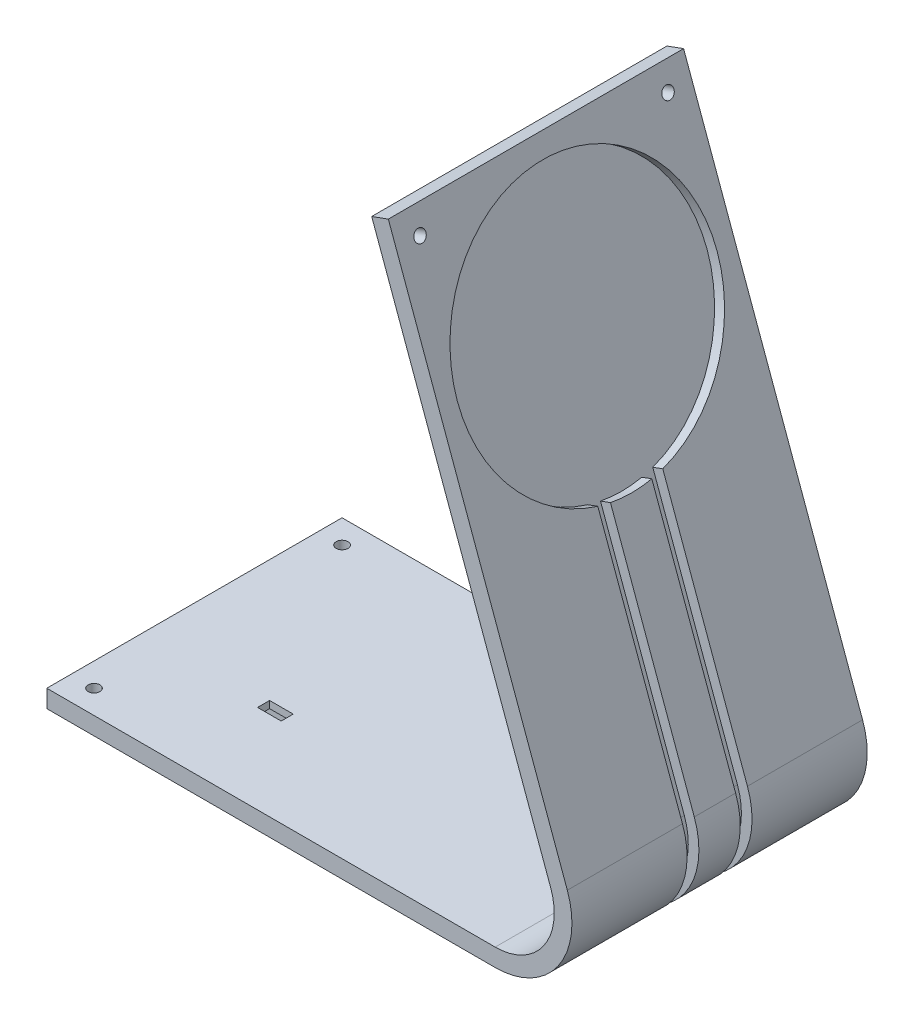
SolidWorks part; units mm, degrees
ref_plane "前视基准面" through (0, 0, 0) normal (0, 0, 1) x (1, 0, 0)
ref_plane "上视基准面" through (0, 0, 0) normal (0, 1, 0) x (1, 0, 0)
ref_plane "右视基准面" through (0, 0, 0) normal (1, 0, 0) x (0, 0, -1)
other "Configuration Table"
sketch "草图2" plane through (0, 0, 0) normal (0, 0, 1) x (1, 0, 0)
  line L0 (-42.6188, 0) -> (33.3109, 0)
  line L5 (42.7078, 13.4202) -> (12.3985, 96.6944)
  line L6 (42.7078, 13.4202) -> (9.2861, 105.2456) construction
  line L7 (-42.6188, -5) -> (-42.6188, 0) construction
  line L8 (33.3109, 0) -> (33.3109, -1) construction
  line L10 (15.2773, 97.8486) -> (12.3643, 96.7883) construction
  line L11 (-42.6188, 0) -> (33.3109, 0) construction
  arc A0 (33.3109, 0) -> (42.7078, 13.4202) centre (33.3109, 10) ccw
  dimension "D2" = 10
  dimension "D1" = 0.1
extrude "整体拉伸-薄壁1" add sketch "草图2" along normal mid plane 50 thin
sketch "草图4" plane through (44.8442, 16.3219, 0) normal (0.9397, 0.342, 0) x (0, 0, -1)
  line L0 (-25, 86.6225) -> (25, 86.6225) construction
  circle A0 centre (0, 61.2225) radius 22
  dimension "D1" = 44
  dimension "D2" = 25.4
extrude "中间圆切除-拉伸1" cut sketch "草图4" against normal blind 1.8
sketch "草图3" plane through (0, 0, 0) normal (0, 0, 1) x (1, 0, 0)
  line L0 (45.5269, 14.4463) -> (15.2176, 97.7204) construction
  line L1 (45.5269, 14.4463) -> (15.2176, 97.7204) construction
  line L2 (-42.6188, -3) -> (33.3109, -3) construction
  line L3 (-42.6188, -3) -> (33.3109, -3) construction
  line L4 (8.763, -1.2) -> (33.3109, -1.2)
  line L5 (43.8354, 13.8306) -> (29.7379, 52.5634)
  line L6 (43.8354, 13.8306) -> (13.5261, 97.1048) construction
  line L7 (-42.6188, -1.2) -> (33.3109, -1.2) construction
  line L9 (29.7379, 52.5634) -> (31.4293, 53.179) construction
  line L16 (29.7379, 52.5634) -> (28.7118, 55.3824)
  arc A0 (33.3109, 0) -> (42.7078, 13.4202) centre (33.3109, 10) ccw construction
  arc A1 (33.3109, -3) -> (45.5269, 14.4463) centre (33.3109, 10) ccw construction
  arc A2 (33.3109, -1.2) -> (43.8354, 13.8306) centre (33.3109, 10) ccw
  dimension "D2" = 3
  dimension "D1" = 1.8
extrude "线槽切除-拉伸-薄壁1" cut sketch "草图3" against normal blind 2 from offset 5.5 thin
mirror "镜向1" about plane through (0, 0, 0) normal (0, 0, 1) of "线槽切除-拉伸-薄壁1"
sketch "草图5" plane through (44.8442, 16.3219, 0) normal (0.9397, 0.342, 0) x (0, 0, -1)
  line L0 (-25, -1.9961) -> (-25, 86.6225) construction
  line L1 (-25, 86.6225) -> (25, 86.6225) construction
  circle A0 centre (-21, 82.6225) radius 1
  dimension "D1" = 2
  dimension "D3" = 4
  dimension "D2" = 4
extrude "螺丝孔切除-拉伸2" cut sketch "草图5" against normal up to next
mirror "镜向2" about plane through (0, 0, 0) normal (0, 0, 1) of "螺丝孔切除-拉伸2"
sketch "草图6" plane through (0, 0, 0) normal (0, 1, 0) x (1, 0, 0)
  line L0 (-42.6188, -25) -> (33.3109, -25) construction
  line L1 (-42.6188, -25) -> (-42.6188, 25) construction
  circle A0 centre (-38.6188, -21) radius 1
  dimension "D1" = 2
  dimension "D2" = 4
  dimension "D3" = 4
extrude "下螺丝孔切除-拉伸3" cut sketch "草图6" against normal up to next
mirror "镜向3" about plane through (0, 0, 0) normal (0, 0, 1) of "下螺丝孔切除-拉伸3"
sketch "草图7" plane through (0, -3, 0) normal (0, -1, 0) x (1, 0, 0)
  line L1 (-40.9188, -5.9) -> (-26.9188, -5.9)
  line L2 (-42.6188, -4.6) -> (-42.6188, 4.6)
  line L3 (-40.9188, 5.9) -> (-26.9188, 5.9)
  line L4 (-26.9188, -5.9) -> (-26.9188, 5.9)
  line L7 (-42.6188, -4.6) -> (-40.9188, -4.6)
  line L9 (-42.6188, 4.6) -> (-40.9188, 4.6)
  line L11 (-40.9188, 4.6) -> (-40.9188, 5.9)
  line L12 (-40.9188, -4.6) -> (-40.9188, -5.9)
  line L14 (-34.1188, -4.5) -> (-41.6188, -4.5) construction
  line L15 (-42.6188, 25) -> (-42.6188, -25) construction
  line L18 (-27.0188, 5.8) -> (-40.8188, 5.8) construction
  line L19 (-40.8188, -5.8) -> (-27.0188, -5.8) construction
  line L20 (-27.0188, -5.8) -> (-27.0188, 5.8) construction
  line L21 (-40.8188, 5.8) -> (-40.8188, 4.5) construction
  dimension "D1" = 0.1
  dimension "D2" = 9.2
  dimension "D3" = 0.1
  dimension "D4" = 0.1
  dimension "D5" = 0.1
  dimension "D6" = 0.1
extrude "切除-拉伸1" cut sketch "草图7" against normal blind 1.8
sketch "草图8" plane through (0, -1.2, 0) normal (0, -1, 0) x (1, 0, 0)
  line L1 (-42.6188, -4.6) -> (-40.9188, -4.6)
  line L2 (-42.6188, -4.6) -> (-42.6188, 4.6)
  line L3 (-42.6188, 4.6) -> (-40.9188, 4.6)
  line L4 (-40.9188, -4.6) -> (-40.9188, 4.6)
extrude "凸台-拉伸1" add sketch "草图8" along normal blind 1.7
sketch "草图12" plane through (0, -3, 0) normal (0, -1, 0) x (1, 0, 0)
  line L1 (-10.1, -8.1) -> (-10.1, -10.6)
  line L2 (-10.1, -10.6) -> (15.1, -10.6)
  line L3 (15.1, -10.6) -> (15.1, 10.6)
  line L4 (15.1, 10.6) -> (-10.1, 10.6)
  line L5 (-13.1, 8.1) -> (-13.1, -8.1)
  line L7 (-13.1, -8.1) -> (-10.1, -8.1)
  line L8 (-13.1, 8.1) -> (-10.1, 8.1)
  line L9 (-10.1, 8.1) -> (-10.1, 10.6)
  line L10 (-10, 8) -> (-13, 8) construction
  line L11 (-10, 10.5) -> (-10, 8) construction
  line L12 (7, 10.5) -> (-10, 10.5) construction
  line L13 (15, -3.5) -> (15, 3.5) construction
  line L14 (-10, -10.5) -> (7, -10.5) construction
  line L15 (-10, -8) -> (-10, -10.5) construction
  line L16 (-13, -8) -> (-10, -8) construction
  line L17 (-13, 8) -> (-13, -8) construction
  dimension "D1" = 0.1
  dimension "D2" = 0.1
  dimension "D3" = 0.1
  dimension "D4" = 0.1
  dimension "D5" = 0.1
  dimension "D6" = 0.1
  dimension "D7" = 0.1
  dimension "D8" = 0.1
extrude "零件切除-拉伸2" cut sketch "草图12" against normal blind 2
sketch "草图14" plane through (0, -3, 0) normal (0, -1, 0) x (1, 0, 0)
  line L0 (-13.1, 8.1) -> (-13.1, -8.1) construction
  line L1 (-26.9188, -8.1) -> (-13.1, -8.1)
  line L2 (-26.9188, -8.1) -> (-26.9188, 10.8)
  line L3 (-26.9188, 10.8) -> (-13.1, 10.8)
  line L4 (-13.1, -8.1) -> (-13.1, 10.8)
  line L5 (-24.2094, 10.7) -> (-15.7094, 10.7) construction
  line L6 (-13.1, -8.1) -> (-10.1, -8.1) construction
  line L8 (-26.9188, -5.9) -> (-26.9188, 5.9) construction
  dimension "D1" = 0.1
extrude "切除-拉伸3" cut sketch "草图14" against normal blind 1.8
sketch "草图15" plane through (0, -1.2, 0) normal (0, -1, 0) x (1, 0, 0)
  line L0 (-13.1, 10.8) -> (-26.9188, 10.8) construction
  line L1 (-25.3094, 6.1) -> (-14.6094, 6.1)
  line L2 (-25.3094, 6.1) -> (-25.3094, 10.8)
  line L3 (-25.3094, 10.8) -> (-24.3094, 10.8)
  line L4 (-14.6094, 6.1) -> (-14.6094, 10.8)
  line L5 (-24.3094, 7.1) -> (-15.6094, 7.1)
  line L6 (-24.3094, 7.1) -> (-24.3094, 10.8)
  line L8 (-15.6094, 7.1) -> (-15.6094, 10.8)
  line L9 (-15.6094, 10.8) -> (-14.6094, 10.8)
  line L10 (-24.2094, 7.2) -> (-24.2094, 10.7) construction
  line L11 (-15.7094, 10.7) -> (-15.7094, 7.2) construction
  line L12 (-15.7094, 7.2) -> (-24.2094, 7.2) construction
  point P15 (-14.6094, 8.45)
  dimension "D1" = 0.1
  dimension "D2" = 0.1
  dimension "D3" = 1
  dimension "D4" = 1
  dimension "D5" = 1
  dimension "D6" = 0.1
extrude "凸台-拉伸2" add sketch "草图15" along normal up to surface (1.8 mm away) up to face at (-38.6188, -3, 22)
sketch "草图16" plane through (0, 0, 0) normal (0, 1, 0) x (1, 0, 0)
  line L0 (-18.1594, -9.77) -> (-18.1594, -8.13) construction
  line L1 (-17.9594, -7.93) -> (-21.9594, -7.93)
  line L2 (-17.9594, -7.93) -> (-17.9594, -9.97)
  line L3 (-17.9594, -9.97) -> (-21.9594, -9.97)
  line L4 (-21.9594, -7.93) -> (-21.9594, -9.97)
  line L5 (-21.7594, -9.77) -> (-19.9594, -9.77) construction
  line L6 (-18.1594, -8.13) -> (-19.9594, -8.13) construction
  line L7 (-21.7594, -8.13) -> (-21.7594, -9.77) construction
  dimension "D1" = 0.2
  dimension "D2" = 0.2
  dimension "D3" = 0.2
  dimension "D4" = 0.2
extrude "切除-拉伸4" cut sketch "草图16" against normal up to surface (1.2 mm away) up to face at (-23.7424, -1.2, 3.6385)
